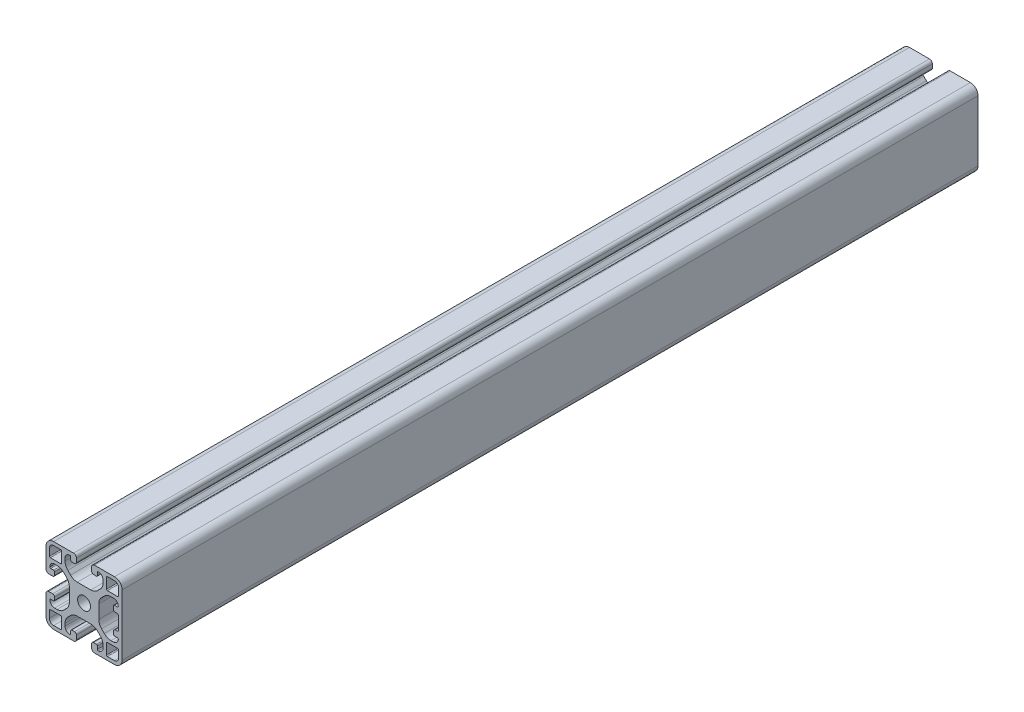
SolidWorks part; units mm, degrees
ref_plane "Piano frontale" through (0, 0, 0) normal (0, 0, 1) x (1, 0, 0)
ref_plane "Piano superiore" through (0, 0, 0) normal (0, 1, 0) x (1, 0, 0)
ref_plane "Piano destro" through (0, 0, 0) normal (1, 0, 0) x (0, 0, -1)
ref_plane "Piano1" through (0, 0, -340) normal (0, 0, -1) x (-1, 0, 0)
sketch "Schizzo1" plane through (0, 0, -340) normal (0, 0, -1) x (-1, 0, 0)
  line L0 (-12.3, -18.2) -> (-16, -18.2)
  line L1 (-18.2, -16) -> (-18.2, -12.3)
  line L2 (-17.7, -11.8) -> (-12.3, -11.8)
  line L3 (-11.8, -12.3) -> (-11.8, -17.7)
  line L4 (-11.8, 17.7) -> (-11.8, 12.3)
  line L5 (-12.3, 11.8) -> (-17.7, 11.8)
  line L6 (-18.2, 12.3) -> (-18.2, 16)
  line L7 (-16, 18.2) -> (-12.3, 18.2)
  line L8 (18.2, 16) -> (18.2, 12.3)
  line L9 (17.7, 11.8) -> (12.3, 11.8)
  line L10 (11.8, 12.3) -> (11.8, 17.7)
  line L11 (12.3, 18.2) -> (16, 18.2)
  line L12 (6.5, -15.5) -> (5, -15.5)
  line L13 (4, -16.5) -> (4, -18.5)
  line L14 (5.5, -20) -> (16, -20)
  line L15 (20, -16) -> (20, -5.5)
  line L16 (18.5, -4) -> (16.5, -4)
  line L17 (15.5, -5) -> (15.5, -6.5)
  line L18 (16, -7) -> (17.55, -7)
  line L19 (18, -7.45) -> (18, -7.5)
  line L20 (15.5, -10) -> (14.1924, -10)
  line L21 (10.6569, -8.5355) -> (9.2145, -7.0931)
  line L22 (7.75, -3.5576) -> (7.75, 3.5576)
  line L23 (9.2145, 7.0931) -> (10.6569, 8.5355)
  line L24 (14.1924, 10) -> (15.5, 10)
  line L25 (18, 7.5) -> (18, 7.45)
  line L26 (17.55, 7) -> (16, 7)
  line L27 (15.5, 6.5) -> (15.5, 5)
  line L28 (16.5, 4) -> (18.5, 4)
  line L29 (20, 5.5) -> (20, 16)
  line L30 (16, 20) -> (5.5, 20)
  line L31 (4, 18.5) -> (4, 16.5)
  line L32 (5, 15.5) -> (6.5, 15.5)
  line L33 (7, 16) -> (7, 17.55)
  line L34 (7.45, 18) -> (7.5, 18)
  line L35 (10, 15.5) -> (10, 14.1924)
  line L36 (8.5355, 10.6569) -> (7.0931, 9.2145)
  line L37 (3.5576, 7.75) -> (-3.5576, 7.75)
  line L38 (-7.0931, 9.2145) -> (-8.5355, 10.6569)
  line L39 (-10, 14.1924) -> (-10, 15.5)
  line L40 (-7.5, 18) -> (-7.45, 18)
  line L41 (-7, 17.55) -> (-7, 16)
  line L42 (-6.5, 15.5) -> (-5, 15.5)
  line L43 (-4, 16.5) -> (-4, 18.5)
  line L44 (-5.5, 20) -> (-16, 20)
  line L45 (-20, 16) -> (-20, -16)
  line L46 (-16, -20) -> (-5.5, -20)
  line L47 (-4, -18.5) -> (-4, -16.5)
  line L48 (-5, -15.5) -> (-6.5, -15.5)
  line L49 (-7, -16) -> (-7, -17.55)
  line L50 (-7.45, -18) -> (-7.5, -18)
  line L51 (-10, -15.5) -> (-10, -14.1924)
  line L52 (-8.5355, -10.6569) -> (-7.0931, -9.2145)
  line L53 (-3.5576, -7.75) -> (3.5576, -7.75)
  line L54 (7.0931, -9.2145) -> (8.5355, -10.6569)
  line L55 (10, -14.1924) -> (10, -15.5)
  line L56 (7.5, -18) -> (7.45, -18)
  line L57 (7, -17.55) -> (7, -16)
  line L58 (18.2, -12.3) -> (18.2, -16)
  line L59 (16, -18.2) -> (12.3, -18.2)
  line L60 (11.8, -17.7) -> (11.8, -12.3)
  line L61 (12.3, -11.8) -> (17.7, -11.8)
  line L62 (-16, 7) -> (-17.5, 7)
  line L63 (-15.5, 10) -> (-14.1924, 10)
  line L64 (-10.6569, 8.5355) -> (-9.2145, 7.0931)
  line L65 (-7.75, 3.5576) -> (-7.75, -3.5576)
  line L66 (-9.2145, -7.0931) -> (-10.6569, -8.5355)
  line L67 (-14.1924, -10) -> (-15.5, -10)
  line L68 (-17.5, -7) -> (-16, -7)
  line L69 (-15.5, -6.5) -> (-15.5, -5)
  line L70 (-16.5, -4) -> (-17.5, -4)
  line L71 (-18, -3.5) -> (-18, 3.5)
  line L72 (-17.5, 4) -> (-16.5, 4)
  line L73 (-15.5, 5) -> (-15.5, 6.5)
  arc A0 (-16, -18.2) -> (-18.2, -16) centre (-16, -16) cw
  arc A1 (-18.2, -12.3) -> (-17.7, -11.8) centre (-17.7, -12.3) cw
  arc A2 (-12.3, -11.8) -> (-11.8, -12.3) centre (-12.3, -12.3) cw
  arc A3 (-11.8, -17.7) -> (-12.3, -18.2) centre (-12.3, -17.7) cw
  arc A4 (-12.3, 18.2) -> (-11.8, 17.7) centre (-12.3, 17.7) cw
  arc A5 (-11.8, 12.3) -> (-12.3, 11.8) centre (-12.3, 12.3) cw
  arc A6 (-17.7, 11.8) -> (-18.2, 12.3) centre (-17.7, 12.3) cw
  arc A7 (-18.2, 16) -> (-16, 18.2) centre (-16, 16) cw
  arc A8 (16, 18.2) -> (18.2, 16) centre (16, 16) cw
  arc A9 (18.2, 12.3) -> (17.7, 11.8) centre (17.7, 12.3) cw
  arc A10 (12.3, 11.8) -> (11.8, 12.3) centre (12.3, 12.3) cw
  arc A11 (11.8, 17.7) -> (12.3, 18.2) centre (12.3, 17.7) cw
  arc A12 (5, -15.5) -> (4, -16.5) centre (5, -16.5) ccw
  arc A13 (4, -18.5) -> (5.5, -20) centre (5.5, -18.5) ccw
  arc A14 (16, -20) -> (20, -16) centre (16, -16) ccw
  arc A15 (20, -5.5) -> (18.5, -4) centre (18.5, -5.5) ccw
  arc A16 (16.5, -4) -> (15.5, -5) centre (16.5, -5) ccw
  arc A17 (15.5, -6.5) -> (16, -7) centre (16, -6.5) ccw
  arc A18 (17.55, -7) -> (18, -7.45) centre (17.55, -7.45) cw
  arc A19 (18, -7.5) -> (15.5, -10) centre (15.5, -7.5) cw
  arc A20 (14.1924, -10) -> (10.6569, -8.5355) centre (14.1924, -5) cw
  arc A21 (9.2145, -7.0931) -> (7.75, -3.5576) centre (12.75, -3.5576) cw
  arc A22 (7.75, 3.5576) -> (9.2145, 7.0931) centre (12.75, 3.5576) cw
  arc A23 (10.6569, 8.5355) -> (14.1924, 10) centre (14.1924, 5) cw
  arc A24 (15.5, 10) -> (18, 7.5) centre (15.5, 7.5) cw
  arc A25 (18, 7.45) -> (17.55, 7) centre (17.55, 7.45) cw
  arc A26 (16, 7) -> (15.5, 6.5) centre (16, 6.5) ccw
  arc A27 (15.5, 5) -> (16.5, 4) centre (16.5, 5) ccw
  arc A28 (18.5, 4) -> (20, 5.5) centre (18.5, 5.5) ccw
  arc A29 (20, 16) -> (16, 20) centre (16, 16) ccw
  arc A30 (5.5, 20) -> (4, 18.5) centre (5.5, 18.5) ccw
  arc A31 (4, 16.5) -> (5, 15.5) centre (5, 16.5) ccw
  arc A32 (6.5, 15.5) -> (7, 16) centre (6.5, 16) ccw
  arc A33 (7, 17.55) -> (7.45, 18) centre (7.45, 17.55) cw
  arc A34 (7.5, 18) -> (10, 15.5) centre (7.5, 15.5) cw
  arc A35 (10, 14.1924) -> (8.5355, 10.6569) centre (5, 14.1924) cw
  arc A36 (7.0931, 9.2145) -> (3.5576, 7.75) centre (3.5576, 12.75) cw
  arc A37 (-3.5576, 7.75) -> (-7.0931, 9.2145) centre (-3.5576, 12.75) cw
  arc A38 (-8.5355, 10.6569) -> (-10, 14.1924) centre (-5, 14.1924) cw
  arc A39 (-10, 15.5) -> (-7.5, 18) centre (-7.5, 15.5) cw
  arc A40 (-7.45, 18) -> (-7, 17.55) centre (-7.45, 17.55) cw
  arc A41 (-7, 16) -> (-6.5, 15.5) centre (-6.5, 16) ccw
  arc A42 (-5, 15.5) -> (-4, 16.5) centre (-5, 16.5) ccw
  arc A43 (-4, 18.5) -> (-5.5, 20) centre (-5.5, 18.5) ccw
  arc A44 (-16, 20) -> (-20, 16) centre (-16, 16) ccw
  arc A45 (-20, -16) -> (-16, -20) centre (-16, -16) ccw
  arc A46 (-5.5, -20) -> (-4, -18.5) centre (-5.5, -18.5) ccw
  arc A47 (-4, -16.5) -> (-5, -15.5) centre (-5, -16.5) ccw
  arc A48 (-6.5, -15.5) -> (-7, -16) centre (-6.5, -16) ccw
  arc A49 (-7, -17.55) -> (-7.45, -18) centre (-7.45, -17.55) cw
  arc A50 (-7.5, -18) -> (-10, -15.5) centre (-7.5, -15.5) cw
  arc A51 (-10, -14.1924) -> (-8.5355, -10.6569) centre (-5, -14.1924) cw
  arc A52 (-7.0931, -9.2145) -> (-3.5576, -7.75) centre (-3.5576, -12.75) cw
  arc A53 (3.5576, -7.75) -> (7.0931, -9.2145) centre (3.5576, -12.75) cw
  arc A54 (8.5355, -10.6569) -> (10, -14.1924) centre (5, -14.1924) cw
  arc A55 (10, -15.5) -> (7.5, -18) centre (7.5, -15.5) cw
  arc A56 (7.45, -18) -> (7, -17.55) centre (7.45, -17.55) cw
  arc A57 (7, -16) -> (6.5, -15.5) centre (6.5, -16) ccw
  arc A58 (17.7, -11.8) -> (18.2, -12.3) centre (17.7, -12.3) cw
  arc A59 (18.2, -16) -> (16, -18.2) centre (16, -16) cw
  arc A60 (12.3, -18.2) -> (11.8, -17.7) centre (12.3, -17.7) cw
  arc A61 (11.8, -12.3) -> (12.3, -11.8) centre (12.3, -12.3) cw
  circle A62 centre (0, 0) radius 3.4
  arc A63 (-15.5, 6.5) -> (-16, 7) centre (-16, 6.5) ccw
  arc A64 (-17.5, 7) -> (-18, 7.5) centre (-17.5, 7.5) cw
  arc A65 (-18, 7.5) -> (-15.5, 10) centre (-15.5, 7.5) cw
  arc A66 (-14.1924, 10) -> (-10.6569, 8.5355) centre (-14.1924, 5) cw
  arc A67 (-9.2145, 7.0931) -> (-7.75, 3.5576) centre (-12.75, 3.5576) cw
  arc A68 (-7.75, -3.5576) -> (-9.2145, -7.0931) centre (-12.75, -3.5576) cw
  arc A69 (-10.6569, -8.5355) -> (-14.1924, -10) centre (-14.1924, -5) cw
  arc A70 (-15.5, -10) -> (-18, -7.5) centre (-15.5, -7.5) cw
  arc A71 (-18, -7.5) -> (-17.5, -7) centre (-17.5, -7.5) cw
  arc A72 (-16, -7) -> (-15.5, -6.5) centre (-16, -6.5) ccw
  arc A73 (-15.5, -5) -> (-16.5, -4) centre (-16.5, -5) ccw
  arc A74 (-17.5, -4) -> (-18, -3.5) centre (-17.5, -3.5) cw
  arc A75 (-18, 3.5) -> (-17.5, 4) centre (-17.5, 3.5) cw
  arc A76 (-16.5, 4) -> (-15.5, 5) centre (-16.5, 5) ccw
extrude "Estrusione-Estrusione1" add sketch "Schizzo1" against normal blind 450
